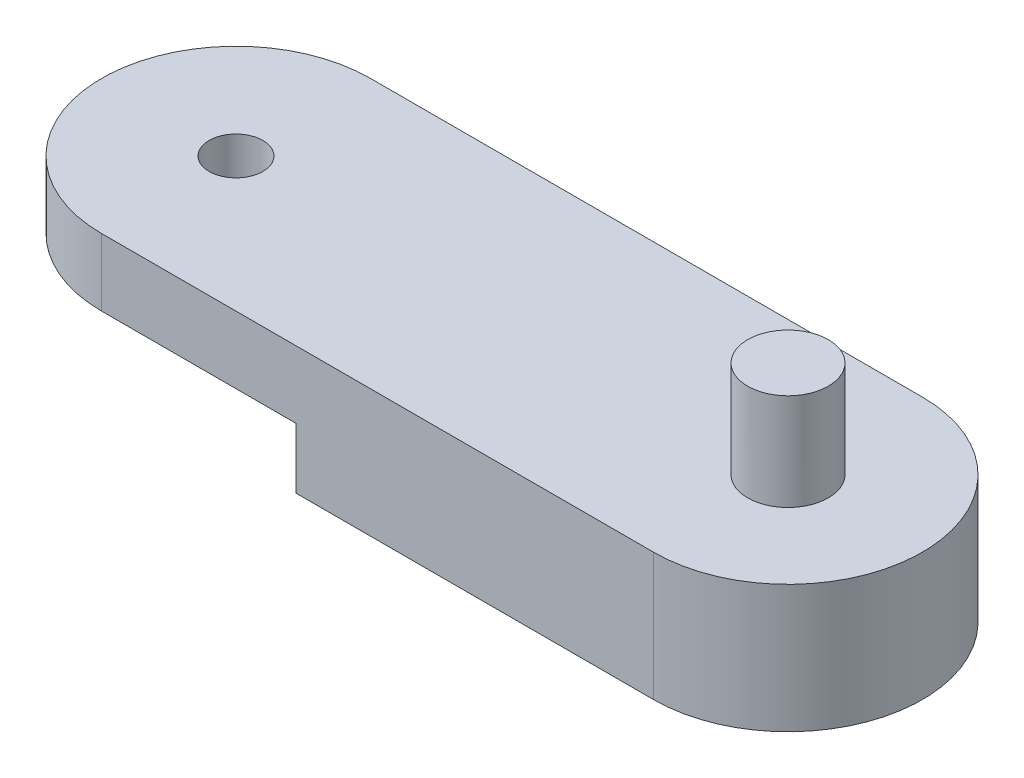
SolidWorks part; units mm, degrees
ref_plane "前视基准面" through (0, 0, 0) normal (0, 0, 1) x (1, 0, 0)
ref_plane "上视基准面" through (0, 0, 0) normal (0, 1, 0) x (1, 0, 0)
ref_plane "右视基准面" through (0, 0, 0) normal (1, 0, 0) x (0, 0, -1)
other "Configuration Table"
sketch "草图1" plane through (0, 0, 0) normal (0, 1, 0) x (1, 0, 0)
  line L0 (0, 0) -> (100, 0) construction
  line L1 (0, 10) -> (100, 10)
  line L2 (0, -10) -> (100, -10)
  arc A0 (0, 10) -> (0, -10) centre (0, 0) ccw
  arc A1 (100, -10) -> (100, 10) centre (100, 0) ccw
  circle A2 centre (0, 0) radius 2
  point P3 (50, 0)
  dimension "D3" = 4
  dimension "D1" = 100
  dimension "D2" = 20
extrude "凸台-拉伸1" add sketch "草图1" along normal blind 5
sketch "草图2" plane through (0, 5, 0) normal (0, 1, 0) x (1, 0, 0)
  circle A0 centre (100, 0) radius 3
extrude "凸台-拉伸2" add sketch "草图2" along normal blind 10
sketch "草图3" plane through (0, 0, 0) normal (0, -1, 0) x (1, 0, 0)
  line L0 (100, -10) -> (0, -10) construction
  line L1 (100, 10) -> (73.4078, 10)
  line L3 (100, -10) -> (73.4078, -10)
  line L4 (73.4078, 10) -> (73.4078, -10)
  arc A0 (100, -10) -> (100, 10) centre (100, 0) ccw
extrude "凸台-拉伸3" add sketch "草图3" along normal blind 4.5
sketch "草图4" plane through (0, -4.5, 0) normal (0, -1, 0) x (1, 0, 0)
  line L1 (79.8492, 2.2886) -> (99.6902, 3.2362)
  line L2 (79.8492, -2.2886) -> (99.6902, -3.2362)
  arc A0 (99.6902, -3.2362) -> (99.6902, 3.2362) centre (100, 0) ccw
  arc A1 (79.8492, 2.2886) -> (79.8492, -2.2886) centre (79.8492, 0) ccw
extrude "切除-拉伸1" cut sketch "草图4" against normal blind 4.5
sketch "草图7" plane through (0, 5, 0) normal (0, 1, 0) x (1, 0, 0)
  line L0 (100, 0) -> (55.0364, 0)
  line L1 (100, 10) -> (0, 10) construction
  line L2 (0, -10) -> (100, -10) construction
  arc A0 (58.9247, 10) -> (58.9247, -10) centre (58.9247, 0) ccw
  circle A1 centre (58.9247, 0) radius 2
  arc M2 (0, 10) -> (0, -10) centre (0, 0) ccw
  line M3 (0, -10) -> (100, -10)
  line M5 (100, 10) -> (0, 10)
  circle M6 centre (0, 0) radius 2
extrude "切除-拉伸2" cut sketch "草图7" against normal blind 10 contours A0 M5 M2 M3 M6
sketch "草图8" plane through (0, 5, 0) normal (0, 1, 0) x (1, 0, 0)
  circle A0 centre (58.9247, 0) radius 2
extrude "切除-拉伸3" cut sketch "草图8" against normal blind 10
sketch "草图9" plane through (0, -4.5, 0) normal (0, -1, 0) x (1, 0, 0)
  line L0 (79.8492, 2.2886) -> (99.379, 4.8101)
  line L1 (79.8492, -2.2886) -> (99.379, -4.8101)
  line L2 (79.8492, -2.2886) -> (99.6902, -3.2362) construction
  arc A0 (99.379, -4.8101) -> (99.379, 4.8101) centre (100, 0) ccw
  arc A1 (79.8492, 2.2886) -> (79.8492, -2.2886) centre (79.8492, 0) ccw construction
  arc A2 (79.8492, 2.2886) -> (79.8492, -2.2886) centre (79.8492, 0) ccw
extrude "切除-拉伸4" cut sketch "草图9" against normal blind 6
sketch "草图10" plane through (0, 15, 0) normal (0, 1, 0) x (1, 0, 0)
  line L1 (82.1012, -23.6917) -> (105.2406, -23.6917)
  line L2 (82.1012, -23.6917) -> (82.1012, 7.6719)
  line L3 (82.1012, 7.6719) -> (105.2406, 7.6719)
  line L4 (105.2406, -23.6917) -> (105.2406, 7.6719)
  line L5 (82.1012, -23.6917) -> (105.2406, 7.6719) construction
  line L6 (82.1012, 7.6719) -> (105.2406, -23.6917) construction
  point P0 (93.6709, -8.0099)
extrude "切除-拉伸7" cut sketch "草图10" against normal blind 2.8
